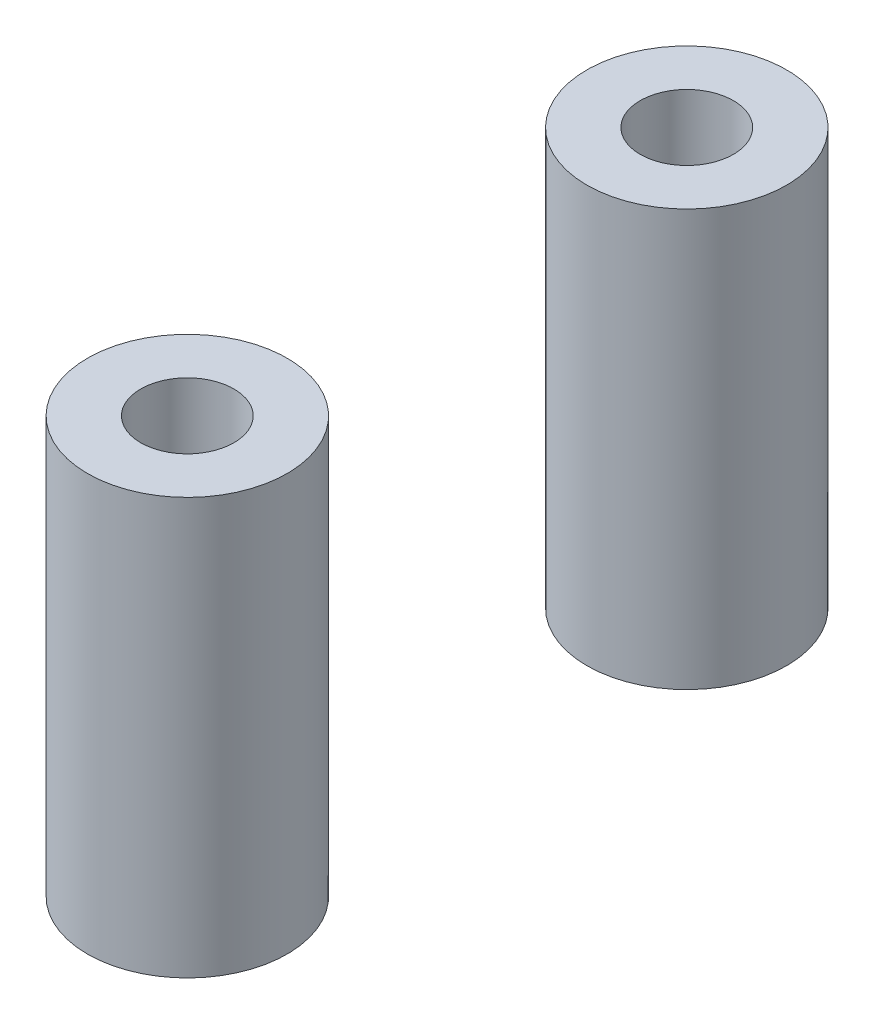
SolidWorks part; units mm, degrees
ref_plane "Front Plane" through (0, 0, 0) normal (0, 0, 1) x (1, 0, 0)
ref_plane "Top Plane" through (0, 0, 0) normal (0, 1, 0) x (1, 0, 0)
ref_plane "Right Plane" through (0, 0, 0) normal (1, 0, 0) x (0, 0, -1)
sketch "Sketch1" plane through (0, 0, 0) normal (0, 1, 0) x (1, 0, 0)
  line L0 (5.1924, 4.619) -> (5.1924, -10.381) construction
  line L1 (-7.8076, 8.119) -> (9.1924, 8.119)
  line L2 (-7.8076, 8.119) -> (-7.8076, -13.881)
  line L3 (-7.8076, -13.881) -> (9.1924, -13.881)
  line L4 (9.1924, 8.119) -> (9.1924, -13.881)
  circle A0 centre (5.1924, 4.619) radius 3
  circle A1 centre (5.1924, -10.381) radius 3
  point P8 (9.1924, -2.881)
  point P9 (5.1924, -2.881)
  dimension "D5" = 6
  dimension "D1" = 17
  dimension "D2" = 22
  dimension "D3" = 15
  dimension "D4" = 4
extrude "Boss-Extrude1" add sketch "Sketch1" along normal blind 12.5
sketch "Sketch2" plane through (0, 12.5, 0) normal (0, 1, 0) x (1, 0, 0)
  circle A0 centre (5.1924, 4.619) radius 1.4
  circle A1 centre (5.1924, -10.381) radius 1.4
  dimension "D1" = 2.8
extrude "Cut-Extrude1" cut sketch "Sketch2" against normal blind 10
